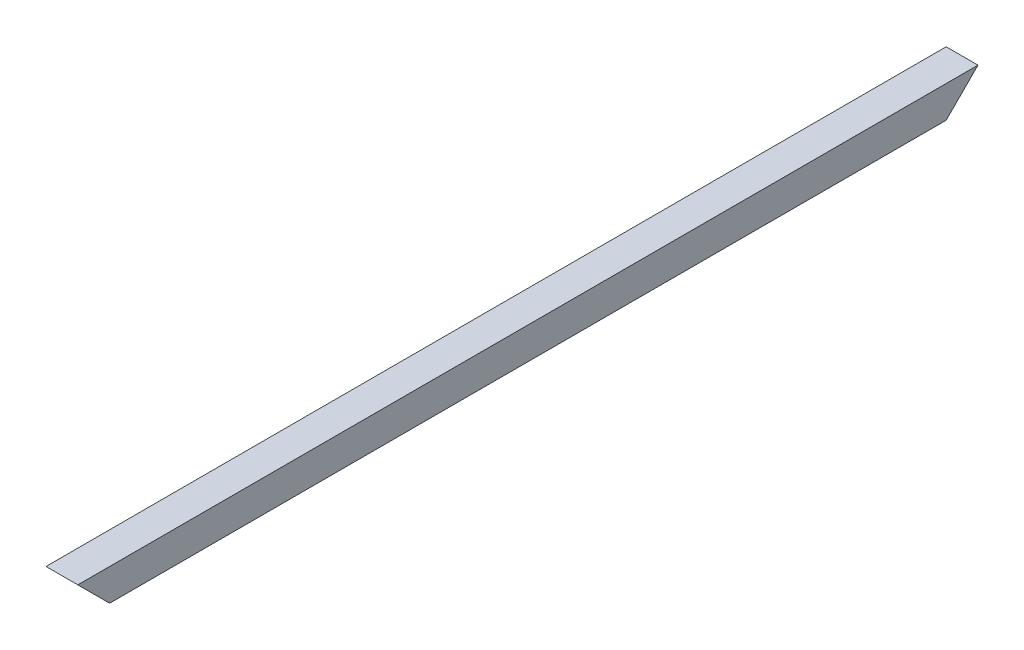
SolidWorks part; units mm, degrees
ref_plane "Front Plane" through (0, 0, 0) normal (0, 0, 1) x (1, 0, 0)
ref_plane "Top Plane" through (0, 0, 0) normal (0, 1, 0) x (1, 0, 0)
ref_plane "Right Plane" through (0, 0, 0) normal (1, 0, 0) x (0, 0, -1)
sketch "Sketch1" plane through (0, 0, 0) normal (0, 0, 1) x (1, 0, 0)
  line L1 (-25, -25) -> (25, -25)
  line L2 (-25, -25) -> (-25, 25)
  line L3 (-25, 25) -> (25, 25)
  line L4 (25, -25) -> (25, 25)
  line L5 (-25, -25) -> (25, 25) construction
  line L6 (-25, 25) -> (25, -25) construction
  line L11 (-23, -23) -> (23, -23)
  line L12 (-23, -23) -> (-23, 23)
  line L13 (-23, 23) -> (23, 23)
  line L14 (23, -23) -> (23, 23)
  line L15 (-23, -23) -> (23, 23) construction
  line L16 (-23, 23) -> (23, -23) construction
  point P0 (0, 0)
  point P6 (0, 0)
  dimension "D1" = 50
  dimension "D2" = 46
extrude "Boss-Extrude1" add sketch "Sketch1" along normal blind 1414.3
sketch "Sketch2" plane through (25, 0, 0) normal (1, 0, 0) x (0, 0, -1)
  line L0 (-1414.3, 25) -> (-1414.3, -25)
  line L1 (-1414.3, -25) -> (-1364.3, -25)
  line L2 (-1414.3, -25) -> (0, -25) construction
  line L3 (-1364.3, -25) -> (-1414.3, 25)
  line L4 (0, 25) -> (0, -25)
  line L5 (0, -25) -> (-50, -25)
  line L6 (-50, -25) -> (0, 25)
extrude "Cut-Extrude1" cut sketch "Sketch2" against normal through all
